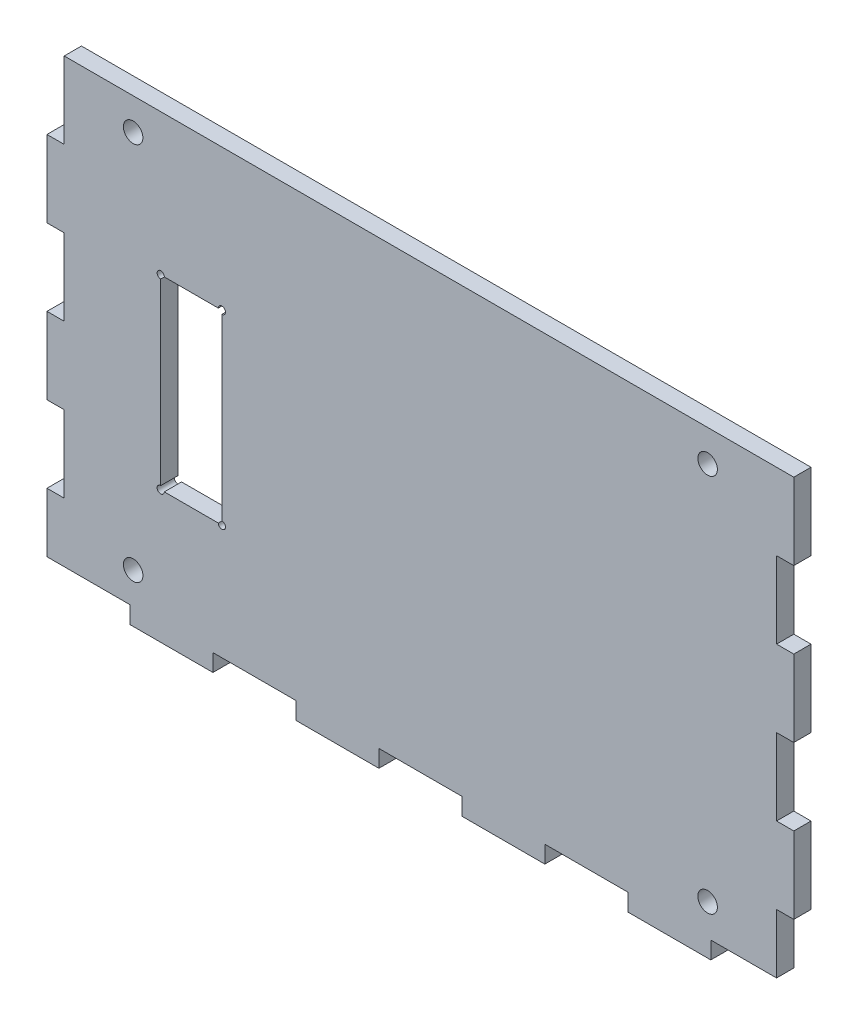
SolidWorks part; units mm, degrees
material "Acrylic (Medium-high impact)"
ref_plane "Front Plane" through (0, 0, 0) normal (0, 0, 1) x (1, 0, 0)
ref_plane "Top Plane" through (0, 0, 0) normal (0, 1, 0) x (1, 0, 0)
ref_plane "Right Plane" through (0, 0, 0) normal (1, 0, 0) x (0, 0, -1)
sketch "Sketch1" plane through (0, 0, 0) normal (0, 0, 1) x (1, 0, 0)
  line L1 (0, 0) -> (130, 0)
  line L2 (0, 0) -> (0, 80)
  line L3 (0, 80) -> (130, 80)
  line L4 (130, 0) -> (130, 80)
  dimension "D1" = 130
  dimension "D2" = 80
extrude "Boss-Extrude1" add sketch "Sketch1" along normal blind 3
sketch "Sketch2" plane through (0, 0, 3) normal (0, 0, 1) x (1, 0, 0)
  line L61 (14.4444, 3) -> (28.8889, 3) construction
  line L62 (0, 0) -> (14.4444, 0)
  line L67 (0, 0) -> (0, 3)
  line L72 (0, 3) -> (14.4444, 3)
  line L77 (14.4444, 0) -> (14.4444, 3)
  line L97 (28.8889, 0) -> (28.8889, 3)
  line L98 (28.8889, 0) -> (43.3333, 0)
  line L107 (43.3333, 0) -> (43.3333, 3)
  line L115 (28.8889, 3) -> (43.3333, 3)
  line L117 (43.3333, 3) -> (57.7778, 3) construction
  line L123 (57.7778, 0) -> (57.7778, 3)
  line L128 (57.7778, 0) -> (72.2222, 0)
  line L129 (72.2222, 0) -> (72.2222, 3)
  line L131 (57.7778, 3) -> (72.2222, 3)
  line L132 (72.2222, 3) -> (86.6667, 3) construction
  line L133 (86.6667, 0) -> (86.6667, 3)
  line L134 (86.6667, 0) -> (101.1111, 0)
  line L135 (101.1111, 0) -> (101.1111, 3)
  line L136 (86.6667, 3) -> (101.1111, 3)
  line L137 (101.1111, 3) -> (115.5556, 3) construction
  line L138 (115.5556, 0) -> (115.5556, 3)
  line L139 (115.5556, 0) -> (130, 0)
  line L142 (130, 0) -> (130, 80) construction
  line L143 (0, 80) -> (0, 0) construction
  line L144 (0, 13.3333) -> (3, 13.3333)
  line L145 (0, 13.3333) -> (0, 26.6667)
  line L146 (130, 3) -> (144.4444, 3) construction
  line L147 (0, 26.6667) -> (3, 26.6667)
  line L148 (3, 13.3333) -> (3, 26.6667)
  line L149 (3, 13.3333) -> (3, 0) construction
  line L150 (0, 40) -> (0, 53.3333)
  line L151 (0, 40) -> (3, 40)
  line L152 (3, 40) -> (3, 53.3333)
  line L153 (0, 53.3333) -> (3, 53.3333)
  line L154 (3, 40) -> (3, 26.6667) construction
  line L155 (0, 66.6667) -> (0, 80)
  line L156 (0, 66.6667) -> (3, 66.6667)
  line L157 (3, 66.6667) -> (3, 80)
  line L158 (0, 80) -> (3, 80)
  line L159 (3, 66.6667) -> (3, 53.3333) construction
  line L160 (130, 80) -> (0, 80) construction
  line L161 (127, 80) -> (127, 66.6667) construction
  line L162 (127, 40) -> (127, 26.6667)
  line L163 (127, 66.6667) -> (130, 66.6667)
  line L164 (127, 66.6667) -> (127, 53.3333)
  line L165 (127, 53.3333) -> (130, 53.3333)
  line L166 (130, 66.6667) -> (130, 53.3333)
  line L167 (127, 40) -> (130, 40)
  line L168 (130, 40) -> (130, 26.6667)
  line L169 (127, 26.6667) -> (130, 26.6667)
  line L170 (127, 53.3333) -> (127, 40) construction
  line L172 (127, 13.3333) -> (130, 13.3333)
  line L173 (130, 13.3333) -> (130, 0)
  line L175 (127, 26.6667) -> (127, 13.3333) construction
  line L183 (115.5556, 3) -> (130, 3) [skipped]
  line L184 (130, 0) -> (130, 3) [skipped]
  line L185 (127, 13.3333) -> (127, 3)
  line L186 (127, 3) -> (115.5556, 3)
  line L187 (127, 0) -> (130, 0) [skipped]
  line L188 (127, 13.3333) -> (127, 0) [skipped]
  dimension "D2" = 3
  dimension "D4" = 3
  dimension "D6" = 3
  dimension "D1" = 5
  dimension "D3" = 3
  dimension "D5" = 3
extrude "Cut-Extrude1" cut sketch "Sketch2" against normal through all
sketch "Sketch3" plane through (0, 0, 3) normal (0, 0, 1) x (1, 0, 0)
  line L0 (0, 66.6667) -> (0, 53.3333) construction
  line L1 (130, 80) -> (3, 80) construction
  line L2 (0, 66.6667) -> (130, 66.6667) construction
  line L3 (65, 66.6667) -> (65, 50066.6667) construction
  line L4 (14.4444, 3) -> (0, 3) construction
  line L5 (15, 74.5) -> (115, 74.5) construction
  line L6 (15, 74.5) -> (15, 8.5) construction
  line L7 (15, 8.5) -> (115, 8.5) construction
  line L8 (115, 74.5) -> (115, 8.5) construction
  circle A0 centre (15, 74.5) radius 1.7
  circle A1 centre (115, 74.5) radius 1.7
  circle A2 centre (15, 8.5) radius 1.7
  circle A3 centre (115, 8.5) radius 1.7
  point P10 (65, 66.6667)
  dimension "D1" = 3.4
  dimension "D2" = 15
  dimension "D3" = 5.5
  dimension "D4" = 5.5
extrude "Cut cornerpiece holes" cut sketch "Sketch3" against normal up to next
sketch "Sketch4" plane through (0, 0, 0) normal (0, 0, -1) x (-1, 0, 0)
  line L0 (-3, 13.3333) -> (-3, 26.6667) construction
  line L1 (-29.825, 55.4) -> (-20.425, 55.4)
  line L2 (-30.45, 54.775) -> (-30.45, 23.625)
  line L3 (-29.825, 23) -> (-20.425, 23)
  line L4 (-19.8, 54.775) -> (-19.8, 23.625)
  line L5 (-43.3333, 3) -> (-28.8889, 3) construction
  arc A0 (-30.45, 23.625) -> (-29.825, 23) centre (-30.45, 23) ccw
  arc A1 (-20.425, 23) -> (-19.8, 23.625) centre (-19.8, 23) ccw
  arc A2 (-19.8, 54.775) -> (-20.425, 55.4) centre (-19.8, 55.4) ccw
  arc A3 (-29.825, 55.4) -> (-30.45, 54.775) centre (-30.45, 55.4) ccw
  dimension "D3" = 1.25
  dimension "D1" = 10.65
  dimension "D2" = 32.4
  dimension "D4" = 16.8
  dimension "D5" = 20
extrude "Cut-Extrude3" cut sketch "Sketch4" against normal up to next
other "Width tolerance" face at (1.5, 26.6667, 1.5) face at (1.5, 53.3333, 1.5) face at (1.5, 66.6667, 1.5) face at (1.5, 40, 1.5) face at (1.5, 13.3333, 1.5) face at (128.5, 66.6667, 1.5) face at (128.5, 40, 1.5) face at (128.5, 53.3333, 1.5) face at (128.5, 26.6667, 1.5) face at (128.5, 13.3333, 1.5) face at (101.1111, 1.5, 1.5) face at (115.5556, 1.5, 1.5) face at (86.6667, 1.5, 1.5) face at (72.2222, 1.5, 1.5) face at (43.3333, 1.5, 1.5) face at (57.7778, 1.5, 1.5) face at (28.8889, 1.5, 1.5) face at (14.4444, 1.5, 1.5) parameters "D1"=0
equation "\"wall_thickness\"= 3mm"
equation "\"D1@Boss-Extrude1\"=\"wall_thickness\""
equation "\"slot_width_tolerance\"= 0.0mm"
equation "\"slot_depth\"= 3mm"
equation "\"D2@Sketch2\"=\"slot_depth\""
equation "\"D4@Sketch2\"=\"slot_depth\""
equation "\"D6@Sketch2\"=\"slot_depth\""
equation "\"D2@Sketch3\"=12.00mm+\"slot_depth\""
equation "\"D1@Width tolerance\"=\"slot_width_tolerance\""
